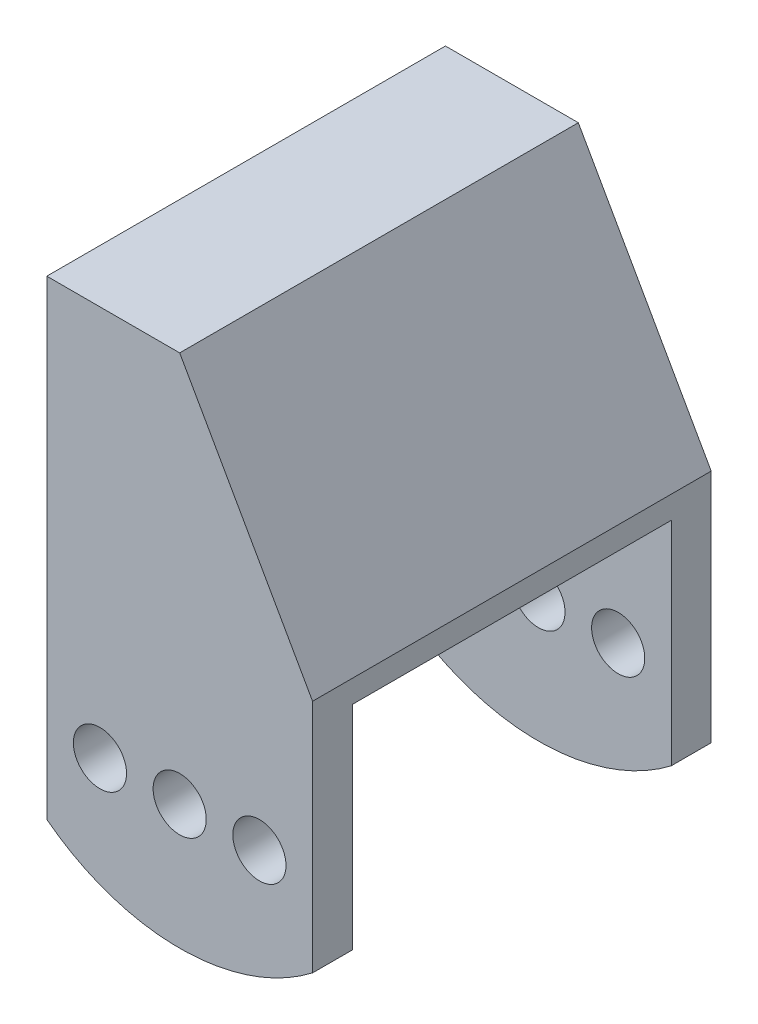
SolidWorks part; units mm, degrees
ref_plane "Front Plane" through (0, 0, 0) normal (0, 0, 1) x (1, 0, 0)
ref_plane "Top Plane" through (0, 0, 0) normal (0, 1, 0) x (1, 0, 0)
ref_plane "Right Plane" through (0, 0, 0) normal (1, 0, 0) x (0, 0, -1)
sketch "Sketch1" plane through (0, 0, 0) normal (0, 0, 1) x (1, 0, 0)
  line L0 (0, 0) -> (-10, -13.0323) construction
  line L1 (0, 0) -> (10, -13.0323) construction
  line L2 (-10, -13.0323) -> (10, -13.0323) construction
  line L9 (-10, 22.3777) -> (0, 22.3777)
  line L10 (-10, -13.0323) -> (-10, 22.3777)
  line L11 (10, 4.6727) -> (10, -13.0323)
  line L12 (0, 22.3777) -> (10, 4.6727)
  arc A0 (-10, -13.0323) -> (10, -13.0323) centre (0, 0) ccw
  circle A2 centre (0, -7.0323) radius 2
  circle A3 centre (6, -7.0323) radius 2
  circle A4 centre (-6, -7.0323) radius 2
  dimension "D6" = 4
  dimension "D7" = 4
  dimension "D10" = 4
  dimension "D1" = 75
  dimension "D2" = 20
  dimension "D3" = 35.41
  dimension "D5" = 6
  dimension "D8" = 6
  dimension "D9" = 6
extrude "Boss-Extrude1" add sketch "Sketch1" along normal blind 30
sketch "Sketch2" plane through (10, 0, 0) normal (1, 0, 0) x (0, 0, -1)
  line L0 (-30, -16.4268) -> (0, -16.4268) construction
  line L1 (-27, -16.4268) -> (-3, -16.4268)
  line L2 (-27, -16.4268) -> (-27, 2.9677)
  line L3 (-27, 2.9677) -> (-3, 2.9677)
  line L4 (-3, -16.4268) -> (-3, 2.9677)
  line L5 (-30, -13.0323) -> (-30, -16.4268) construction
  line L6 (0, -16.4268) -> (0, -13.0323) construction
  line L7 (-30, -13.0323) -> (0, -13.0323) construction
  dimension "D1" = 3
  dimension "D2" = 3
  dimension "D3" = 16
extrude "Cut-Extrude1" cut sketch "Sketch2" against normal through all
sketch "Sketch3" plane through (-10, 0, 0) normal (-1, 0, 0) x (0, 0, 1)
  line L0 (3, 2.9677) -> (27, 2.9677) construction
  circle A0 centre (15, 12.9677) radius 8.9
  circle A1 centre (15, 12.9677) radius 6 construction
  circle A2 centre (15, 18.9677) radius 2
  circle A3 centre (15, 6.9677) radius 2
  circle A4 centre (9, 12.9677) radius 2
  circle A5 centre (21, 12.9677) radius 2
  point P5 (15, 2.9677)
  point P14 (0, 0)
  dimension "D1" = 17.8
  dimension "D2" = 10
  dimension "D3" = 12
  dimension "D4" = 4
  dimension "D5" = 4
  dimension "D6" = 4
  dimension "D7" = 4
extrude "Cut-Extrude2" cut sketch "Sketch3" against normal blind 3
